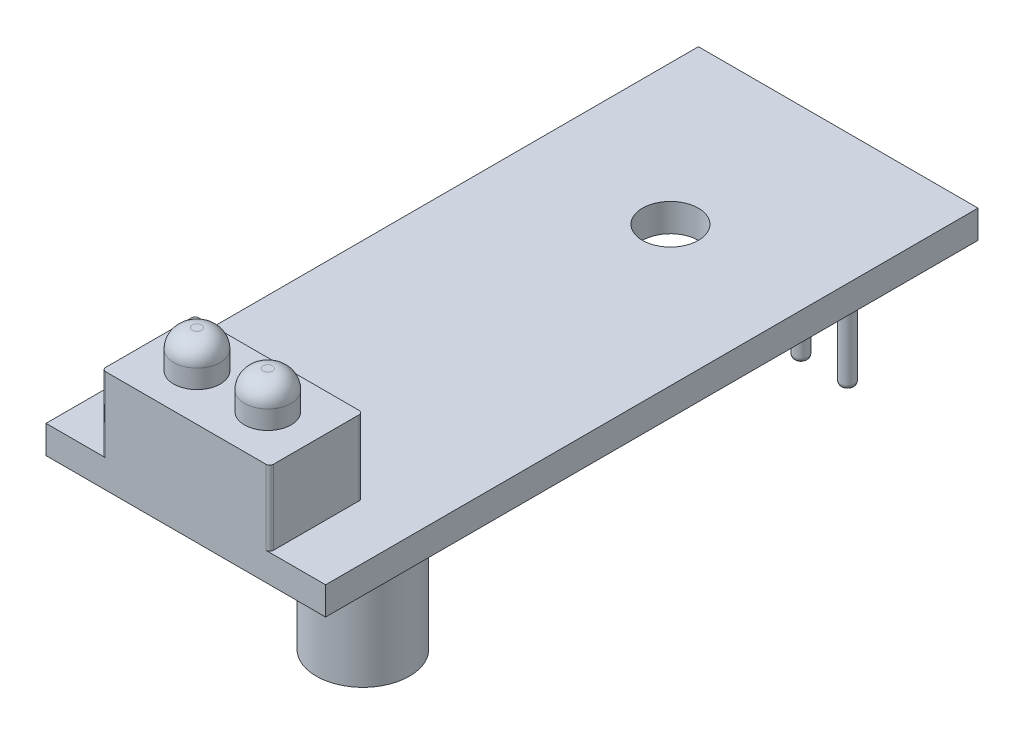
SolidWorks part; units mm, degrees
ref_plane "Front Plane" through (0, 0, 0) normal (0, 0, 1) x (1, 0, 0)
ref_plane "Top Plane" through (0, 0, 0) normal (0, 1, 0) x (1, 0, 0)
ref_plane "Right Plane" through (0, 0, 0) normal (1, 0, 0) x (0, 0, -1)
sketch "Sketch1" plane through (0, 0, 0) normal (0, 1, 0) x (1, 0, 0)
  line L1 (7.5, -17.5) -> (-7.5, -17.5)
  line L2 (7.5, -17.5) -> (7.5, 17.5)
  line L3 (7.5, 17.5) -> (-7.5, 17.5)
  line L4 (-7.5, -17.5) -> (-7.5, 17.5)
  line L5 (7.5, -17.5) -> (-7.5, 17.5) construction
  line L6 (7.5, 17.5) -> (-7.5, -17.5) construction
  point P0 (0, 0)
  dimension "D1" = 35
  dimension "D2" = 15
extrude "Boss-Extrude1" add sketch "Sketch1" along normal blind 1.5
sketch "Sketch2" plane through (0, 1.5, 0) normal (0, 1, 0) x (1, 0, 0)
  line L0 (-7.5, 17.5) -> (-7.5, -17.5) construction
  line L1 (-4.5, -12.5) -> (4.5, -12.5)
  line L2 (-4.5, -12.5) -> (-4.5, -17.5)
  line L3 (-4.5, -17.5) -> (4.5, -17.5)
  line L4 (4.5, -12.5) -> (4.5, -17.5)
  line L5 (-4.5, -12.5) -> (4.5, -17.5) construction
  line L6 (-4.5, -17.5) -> (4.5, -12.5) construction
  line L7 (7.5, -17.5) -> (7.5, 17.5) construction
  line L8 (-7.5, -17.5) -> (7.5, -17.5) construction
  point P0 (0, -15)
  dimension "D1" = 3
  dimension "D2" = 3
  dimension "D3" = 0
  dimension "D4" = 5
extrude "Boss-Extrude2" add sketch "Sketch2" along normal blind 4
fillet "Fillet1" radius 0.2 4 edges at (4.5, 3.5, 12.5) (-4.5, 3.5, 12.5)
sketch "Sketch3" plane through (0, 5.5, 0) normal (0, 1, 0) x (1, 0, 0)
  line L0 (0, 0) -> (0, -17.5) construction
  line L1 (-4.3, -17.5) -> (4.3, -17.5) construction
  circle A0 centre (-1.9, -15) radius 1.25
  circle A1 centre (1.9, -15) radius 1.25
  point P9 (0, -15.0044)
  dimension "D1" = 2.5
  dimension "D3" = 1.9
  dimension "D2" = 2.5
extrude "Boss-Extrude3" add sketch "Sketch3" along normal blind 2
fillet "Fillet2" radius 1 2 edges at (1.9, 7.5, 13.75) (-1.9, 7.5, 16.25)
sketch "Sketch4" plane through (0, 0, 0) normal (0, -1, 0) x (1, 0, 0)
  line L0 (-7.5, 17.5) -> (7.5, 17.5) construction
  line L1 (-6.5, 12.5) -> (-3.5, 12.5)
  line L2 (-6.5, 12.5) -> (-6.5, 9.5)
  line L3 (-6.5, 9.5) -> (-3.5, 9.5)
  line L4 (-3.5, 12.5) -> (-3.5, 9.5)
  line L5 (-6.5, 12.5) -> (-3.5, 9.5) construction
  line L6 (-6.5, 9.5) -> (-3.5, 12.5) construction
  line L7 (-7.5, -17.5) -> (-7.5, 17.5) construction
  point P0 (-5, 11)
  dimension "D1" = 3
  dimension "D2" = 3
  dimension "D3" = 5
  dimension "D4" = 1
extrude "Boss-Extrude4" add sketch "Sketch4" along normal blind 1
sketch "Sketch5" plane through (0, 0, 0) normal (0, -1, 0) x (1, 0, 0)
  line L0 (-7.5, 17.5) -> (7.5, 17.5) construction
  line L2 (7.5, 17.5) -> (7.5, -17.5) construction
  circle A0 centre (2.5, 10.5) radius 2.5
  point P6 (7.5, 9.6695)
  dimension "D1" = 5
  dimension "D3" = 5
  dimension "D2" = 7
extrude "Boss-Extrude5" add sketch "Sketch5" along normal blind 7.5
sketch "Sketch6" plane through (0, 0, 0) normal (0, -1, 0) x (1, 0, 0)
  line L0 (7.5, -17.5) -> (-7.5, -17.5) construction
  line L1 (-5, -13.1) -> (-2.6, -13.1)
  line L2 (-5, -13.1) -> (-5, -15.5)
  line L3 (-5, -15.5) -> (-2.6, -15.5)
  line L4 (-2.6, -13.1) -> (-2.6, -15.5)
  line L5 (-5, -13.1) -> (-2.6, -15.5) construction
  line L6 (-5, -15.5) -> (-2.6, -13.1) construction
  line L7 (-7.5, -17.5) -> (-7.5, 17.5) construction
  line L8 (-2.5, -13.1) -> (-0.1, -13.1)
  line L9 (-0.1, -13.1) -> (-0.1, -15.5)
  line L10 (-2.5, -15.5) -> (-0.1, -15.5)
  line L11 (-2.5, -13.1) -> (-2.5, -15.5)
  line L12 (0, -13.1) -> (2.4, -13.1)
  line L13 (2.4, -13.1) -> (2.4, -15.5)
  line L14 (0, -15.5) -> (2.4, -15.5)
  line L15 (0, -13.1) -> (0, -15.5)
  line L16 (2.5, -13.1) -> (4.9, -13.1)
  line L17 (4.9, -13.1) -> (4.9, -15.5)
  line L18 (2.5, -15.5) -> (4.9, -15.5)
  line L19 (2.5, -13.1) -> (2.5, -15.5)
  point P0 (-3.8, -14.3)
  dimension "D1" = 2.4
  dimension "D2" = 2.4
  dimension "D3" = 2
  dimension "D4" = 2.5
  dimension "D5" = 4
extrude "Boss-Extrude6" add sketch "Sketch6" along normal blind 2
fillet "Fillet3" radius 0.1 16 edges at (4.9, -1, -15.5) (2.4, -1, -15.5) (-0.1, -1, -15.5) (-2.6, -1, -15.5) (2.5, -1, -15.5) (0, -1, -15.5) (-2.5, -1, -15.5) (-5, -1, -15.5) (4.9, -1, -13.1) (2.5, -1, -13.1) (2.4, -1, -13.1) (0, -1, -13.1) (-0.1, -1, -13.1) (-2.5, -1, -13.1) (-2.6, -1, -13.1) (-5, -1, -13.1)
sketch "Sketch7" plane through (0, -2, 0) normal (0, -1, 0) x (1, 0, 0)
  line L0 (-5, -13.2) -> (-5, -15.4) construction
  line L1 (-2.7, -13.1) -> (-4.9, -13.1) construction
  circle A0 centre (-3.8, -14.3) radius 0.375
  circle A1 centre (-1.3, -14.3) radius 0.375
  circle A2 centre (1.2, -14.3) radius 0.375
  circle A3 centre (3.7, -14.3) radius 0.375
  dimension "D1" = 0.75
  dimension "D2" = 1.2
  dimension "D3" = 1.2
  dimension "D4" = 4
extrude "Boss-Extrude7" add sketch "Sketch7" along normal blind 5
fillet "Fillet4" radius 0.2 4 edges at (3.7, -7, -14.675) (1.2, -7, -14.675) (-1.3, -7, -14.675) (-3.8, -7, -14.675)
sketch "Sketch8" plane through (0, 0, 0) normal (0, -1, 0) x (1, 0, 0)
  line L0 (7.5, -17.5) -> (-7.5, -17.5) construction
  line L1 (7.5, 17.5) -> (7.5, -17.5) construction
  circle A0 centre (0, -8.5) radius 1.5
  dimension "D1" = 3
  dimension "D3" = 7.5
  dimension "D2" = 9
extrude "Cut-Extrude1" cut sketch "Sketch8" against normal through all
